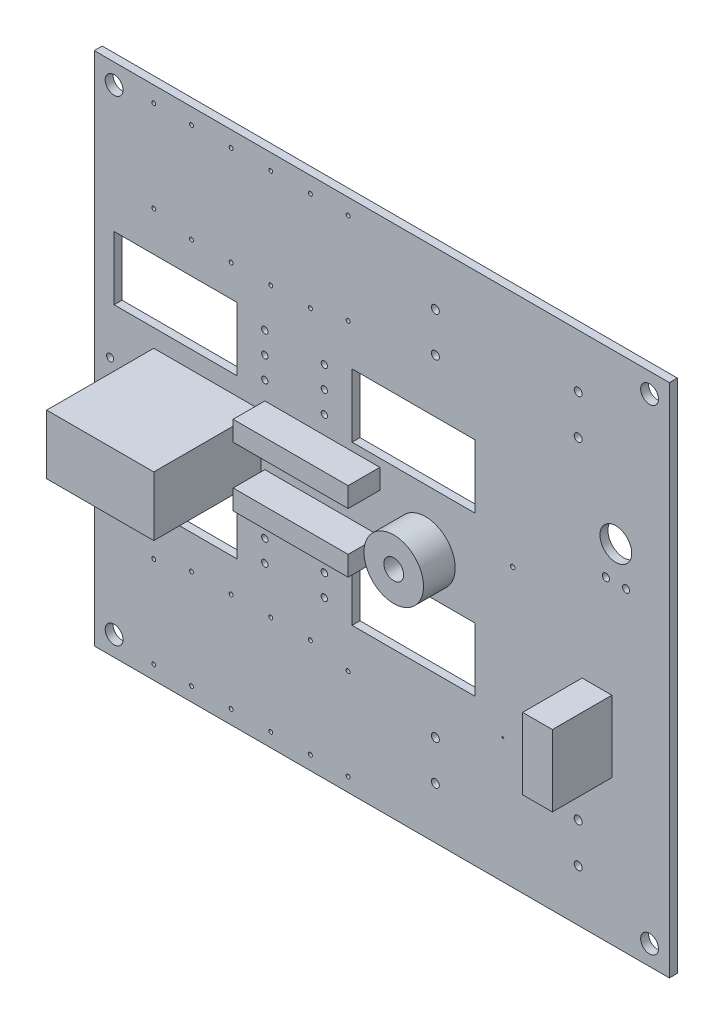
SolidWorks part; units mm, degrees
ref_plane "Спереди" through (0, 0, 0) normal (0, 0, 1) x (1, 0, 0)
ref_plane "Сверху" through (0, 0, 0) normal (0, 1, 0) x (1, 0, 0)
ref_plane "Справа" through (0, 0, 0) normal (1, 0, 0) x (0, 0, -1)
sketch "Эскиз1" plane through (0, 0, 0) normal (0, 0, 1) x (1, 0, 0)
  line L0 (-45.8472, 0) -> (44.7908, 0) construction
  line L1 (0, 38.1356) -> (0, -25.2476) construction
  line L3 (-72.5, -65) -> (72.5, -65)
  line L4 (-72.5, -65) -> (-72.5, 65)
  line L5 (-72.5, 65) -> (72.5, 65)
  line L6 (72.5, -65) -> (72.5, 65)
  line L7 (-67.5, 12) -> (-36.5, 12)
  line L8 (-67.5, 12) -> (-67.5, 28)
  line L9 (-67.5, 28) -> (-36.5, 28)
  line L10 (-36.5, 12) -> (-36.5, 28)
  line L11 (-67.5, -28) -> (-36.5, -28)
  line L12 (-67.5, -28) -> (-67.5, -12)
  line L13 (-67.5, -12) -> (-36.5, -12)
  line L14 (-36.5, -28) -> (-36.5, -12)
  line L15 (-7.5, 12) -> (23.5, 12)
  line L16 (-7.5, 12) -> (-7.5, 28)
  line L17 (-7.5, 28) -> (23.5, 28)
  line L18 (23.5, 12) -> (23.5, 28)
  line L19 (-7.5, -28) -> (23.5, -28)
  line L20 (-7.5, -28) -> (-7.5, -12)
  line L21 (-7.5, -12) -> (23.5, -12)
  line L22 (23.5, -28) -> (23.5, -12)
  circle A0 centre (-67.5, 60) radius 2.25
  circle A1 centre (-67.5, -60) radius 2.25
  circle A2 centre (67.5, 60) radius 2.25
  circle A3 centre (67.5, -60) radius 2.25
  dimension "D3" = 4.5
  dimension "D5" = 5
  dimension "D1" = 145
  dimension "D2" = 130
  dimension "D4" = 5
  dimension "D6" = 5
  dimension "D7" = 5
  dimension "D8" = 16
  dimension "D9" = 37
  dimension "D10" = 31
  dimension "D11" = 77
  dimension "D12" = 65
extrude "Вытянуть1" add sketch "Эскиз1" along normal blind 2
sketch "Эскиз2" plane through (0, 0, 2) normal (0, 0, 1) x (1, 0, 0)
  line L0 (-72.5, 65) -> (-72.5, -65) construction
  line L2 (-57.5, 61) -> (-3.6597, 61) construction
  line L3 (-57.5, 61) -> (-57.5, 38) construction
  line L4 (-48, 61) -> (-48, 36) construction
  line L5 (-38, 61) -> (-38, 36) construction
  line L6 (-28, 61) -> (-28, 36) construction
  line L7 (-18, 61) -> (-18, 36) construction
  line L8 (-8.5, 61) -> (-8.5, 38) construction
  line L9 (-57.5, -61.5) -> (-8.5, -61.5) construction
  line L11 (-48, -36.5) -> (-18, -36.5) construction
  line L12 (-57.5, -38.5) -> (-8.5, -38.5) construction
  line L13 (-72.5, -65) -> (72.5, -65) construction
  line L14 (-57.5, -38.5) -> (-57.5, -61.5) construction
  line L15 (-48, -36.5) -> (-48, -61.5) construction
  line L16 (-38, -36.5) -> (-38, -61.5) construction
  line L17 (-28, -36.5) -> (-28, -61.5) construction
  line L18 (-18, -36.5) -> (-18, -61.5) construction
  line L19 (-8.5, -38.5) -> (-8.5, -61.5) construction
  line L20 (-29.5, -20) -> (-67.5, -20) construction
  line L21 (-67.5, -12) -> (-67.5, -28) construction
  line L22 (-29.5, 20) -> (-64.3087, 20) construction
  line L23 (-67.5, 12) -> (-36.5, 12) construction
  line L24 (-36.5, 28) -> (-67.5, 28) construction
  line L25 (-36.5, -12) -> (-67.5, -12) construction
  line L26 (-67.5, -28) -> (-36.5, -28) construction
  line L27 (-72.5, 65) -> (-72.5, -65) construction
  line L28 (-29.5, 26.7383) -> (-29.5, -20) construction
  line L29 (-14.5, 26.4222) -> (-14.5, -20) construction
  circle A0 centre (-57.5, 61) radius 0.5
  circle A1 centre (-48, 61) radius 0.5
  circle A2 centre (-57.5, 38) radius 0.5
  circle A3 centre (-48, 36) radius 0.5
  circle A4 centre (-38, 61) radius 0.5
  circle A5 centre (-38, 36) radius 0.5
  circle A6 centre (-28, 61) radius 0.5
  circle A7 centre (-28, 36) radius 0.5
  circle A8 centre (-18, 61) radius 0.5
  circle A9 centre (-18, 36) radius 0.5
  circle A10 centre (-8.5, 61) radius 0.5
  circle A11 centre (-8.5, 38) radius 0.5
  circle A12 centre (-8.5, -38.5) radius 0.5
  circle A13 centre (-8.5, -61.5) radius 0.5
  circle A14 centre (-18, -61.5) radius 0.5
  circle A15 centre (-18, -36.5) radius 0.5
  circle A16 centre (-28, -36.5) radius 0.5
  circle A17 centre (-28, -61.5) radius 0.5
  circle A18 centre (-38, -61.5) radius 0.5
  circle A19 centre (-38, -36.5) radius 0.5
  circle A20 centre (-48, -36.5) radius 0.5
  circle A21 centre (-48, -61.5) radius 0.5
  circle A22 centre (-57.5, -61.5) radius 0.5
  circle A23 centre (-57.5, -38.5) radius 0.5
  circle A24 centre (-29.5, 20) radius 0.8
  circle A25 centre (-29.5, -20) radius 0.8
  circle A26 centre (-29.5, 14.55) radius 0.8
  circle A27 centre (-29.5, 25.45) radius 0.8
  circle A28 centre (-29.5, -14.55) radius 0.8
  circle A29 centre (-29.5, -25.45) radius 0.8
  circle A30 centre (-14.5, 20) radius 0.8
  circle A31 centre (-14.5, -20) radius 0.8
  circle A32 centre (-14.5, 14.55) radius 0.8
  circle A33 centre (-14.5, 25.45) radius 0.8
  circle A34 centre (-14.5, -14.866) radius 0.8
  circle A35 centre (-14.5, -25.45) radius 0.8
  dimension "D1" = 1
  dimension "D4" = 9.5
  dimension "D5" = 23
  dimension "D6" = 25
  dimension "D9" = 25
  dimension "D24" = 1.6
  dimension "D25" = 1.6
  dimension "D26" = 5.45
  dimension "D27" = 5.45
  dimension "D28" = 5.45
  dimension "D29" = 5.45
  dimension "D2" = 15
  dimension "D3" = 23
  dimension "D7" = 25
  dimension "D8" = 34.5
  dimension "D10" = 25
  dimension "D11" = 10
  dimension "D12" = 10
  dimension "D13" = 23
  dimension "D14" = 9.5
  dimension "D15" = 25
  dimension "D16" = 3.5
  dimension "D17" = 9.5
  dimension "D18" = 10
  dimension "D19" = 10
  dimension "D20" = 10
  dimension "D21" = 9.5
  dimension "D22" = 43
  dimension "D23" = 43
  dimension "D30" = 5.45
  dimension "D31" = 5.45
  dimension "D32" = 5.45
  dimension "D33" = 58
extrude "Вырез-Вытянуть1" cut sketch "Эскиз2" against normal blind 2
sketch "Эскиз3" plane through (0, 0, 2) normal (0, 0, 1) x (1, 0, 0)
  line L0 (-72.5, 65) -> (-72.5, -65) construction
  line L1 (-72.5, -65) -> (72.5, -65) construction
  line L2 (13.5, 41.5) -> (13.5, 51.5) construction
  line L3 (49.5, 41.5) -> (49.5, 51.5) construction
  line L4 (13.5, -52) -> (13.5, -42) construction
  line L5 (49.5, -52) -> (49.5, -42) construction
  line L6 (-68.5, 0) -> (-54.7244, 0) construction
  line L7 (56.5, 14.5) -> (70.7204, 14.5) construction
  circle A0 centre (13.5, 41.5) radius 1
  circle A1 centre (13.5, 51.5) radius 1
  circle A2 centre (49.5, 41.5) radius 1
  circle A3 centre (49.5, 51.5) radius 1
  circle A4 centre (13.5, -52) radius 1
  circle A5 centre (13.5, -42) radius 1
  circle A6 centre (49.5, -52) radius 1
  circle A7 centre (49.5, -42) radius 1
  circle A8 centre (59, 23) radius 4
  circle A9 centre (-68.5, 0) radius 0.9
  circle A10 centre (-63.42, 0) radius 0.9
  circle A11 centre (56.5, 14.5) radius 0.9
  circle A12 centre (61.58, 14.5) radius 0.9
  dimension "D1" = 2
  dimension "D3" = 106.5
  dimension "D4" = 10
  dimension "D5" = 2
  dimension "D7" = 106.5
  dimension "D9" = 2
  dimension "D11" = 2
  dimension "D14" = 23
  dimension "D17" = 8
  dimension "D20" = 1.8
  dimension "D21" = 5.08
  dimension "D24" = 5.08
  dimension "D2" = 86
  dimension "D6" = 10
  dimension "D8" = 122
  dimension "D10" = 10
  dimension "D12" = 10
  dimension "D13" = 23
  dimension "D15" = 131.5
  dimension "D16" = 88
  dimension "D18" = 4
  dimension "D19" = 65
  dimension "D22" = 79.5
  dimension "D23" = 129
extrude "Вырез-Вытянуть2" cut sketch "Эскиз3" against normal blind 2
sketch "Эскиз4" plane through (0, 0, 2) normal (0, 0, 1) x (1, 0, 0)
  line L0 (-72.5, 65) -> (-72.5, -65) construction
  line L1 (-72.5, -65) -> (72.5, -65) construction
  line L3 (-29.5, 5) -> (-0.5, 5)
  line L4 (-29.5, 5) -> (-29.5, 10)
  line L5 (-29.5, 10) -> (-0.5, 10)
  line L6 (-0.5, 5) -> (-0.5, 10)
  line L7 (-29.5, -10) -> (-0.5, -10)
  line L8 (-29.5, -10) -> (-29.5, -5)
  line L9 (-29.5, -5) -> (-0.5, -5)
  line L10 (-0.5, -10) -> (-0.5, -5)
  circle A0 centre (11, -2.5) radius 7.5
  circle A1 centre (11, -2.5) radius 2.5
  dimension "D1" = 15
  dimension "D2" = 5
  dimension "D3" = 83.5
  dimension "D4" = 62.5
  dimension "D5" = 29
  dimension "D6" = 55
  dimension "D7" = 43
  dimension "D8" = 75
  dimension "D9" = 5
extrude "Вытянуть2" add sketch "Эскиз4" along normal blind 8
sketch "Эскиз5" plane through (0, 0, 2) normal (0, 0, 1) x (1, 0, 0)
  line L0 (-72.5, -65) -> (72.5, -65) construction
  line L1 (-72.5, 65) -> (-72.5, -65) construction
  circle A0 centre (33, 5) radius 0.55
  circle A1 centre (30.5, -33.5) radius 0.25
  dimension "D1" = 1.1
  dimension "D6" = 0.5
  dimension "D2" = 70
  dimension "D3" = 105.5
  dimension "D4" = 31.5
  dimension "D5" = 103
extrude "Вырез-Вытянуть3" cut sketch "Эскиз5" against normal blind 10
sketch "Эскиз6" plane through (0, 0, 2) normal (0, 0, 1) x (1, 0, 0)
  line L0 (72.5, -65) -> (72.5, 65) construction
  line L1 (-57.5, -7.5) -> (-30.5, -7.5)
  line L2 (-57.5, -7.5) -> (-57.5, 7.5)
  line L3 (-57.5, 7.5) -> (-30.5, 7.5)
  line L4 (-30.5, -7.5) -> (-30.5, 7.5)
  line L5 (50.5, -28.5) -> (58, -28.5)
  line L6 (50.5, -28.5) -> (50.5, -10.5)
  line L7 (50.5, -10.5) -> (58, -10.5)
  line L8 (58, -28.5) -> (58, -10.5)
  line L9 (-72.5, -65) -> (72.5, -65) construction
  line L10 (-72.5, 65) -> (-72.5, -65) construction
  dimension "D1" = 14.5
  dimension "D2" = 7.5
  dimension "D3" = 18
  dimension "D4" = 36.5
  dimension "D5" = 27
  dimension "D6" = 15
  dimension "D7" = 57.5
  dimension "D8" = 15
extrude "Вытянуть3" add sketch "Эскиз6" along normal blind 15
sketch "Эскиз7" plane through (0, 0, 17) normal (0, 0, 1) x (1, 0, 0)
  line L4 (-57.5, 7.5) -> (-57.5, -7.5)
  line L5 (-57.5, -7.5) -> (-30.5, -7.5)
  line L6 (-30.5, -7.5) -> (-30.5, 7.5)
  line L7 (-30.5, 7.5) -> (-57.5, 7.5)
  line L8 (-57.5, 7.5) -> (-57.5, -7.5)
  line L9 (-57.5, -7.5) -> (-30.5, -7.5)
  line L10 (-30.5, -7.5) -> (-30.5, 7.5)
  line L11 (-30.5, 7.5) -> (-57.5, 7.5)
  dimension "D1" = 0
extrude "Вытянуть4" add sketch "Эскиз7" along normal blind 12
sketch "Эскиз9" plane through (0, 0, 2) normal (0, 0, 1) x (1, 0, 0)
  line L0 (30.5, -33.5) -> (30.5, -30.8115) construction
  circle A0 centre (29.23, -32.6) radius 0.3
  circle A1 centre (31.77, -32.6) radius 0.3
  circle A2 centre (30.5, -34.7) radius 0.3
  circle A3 centre (30.5, -33.5) radius 0.25 construction
  dimension "D1" = 0.6
  dimension "D2" = 2.54
  dimension "D3" = 2.1
  dimension "D4" = 1.2
extrude "Вытянуть5" add sketch "Эскиз9" against normal blind 6.5
sketch "Эскиз10" plane through (0, 0, -4.5) normal (0, 0, -1) x (-1, 0, 0)
  line L0 (-30.5, -33.5) -> (-30.5, -29.5026) construction
  line L1 (-31.8408, -31.099) -> (-29.1592, -31.099)
  arc A0 (-31.8408, -31.099) -> (-29.1592, -31.099) centre (-30.5, -33.5) ccw
  dimension "D1" = 5.5
extrude "Вытянуть6" add sketch "Эскиз10" along normal blind 0.5
sketch "Эскиз11" plane through (0, 0, -5) normal (0, 0, -1) x (-1, 0, 0)
  circle A0 centre (-30.5, -33.5) radius 2.45
  dimension "D1" = 4.9
extrude "Вытянуть7" add sketch "Эскиз11" along normal blind 8.5
chamfer "Фаска1" distance 0.5 angle 10 1 edges at (28.05, -33.5, -13.5)
